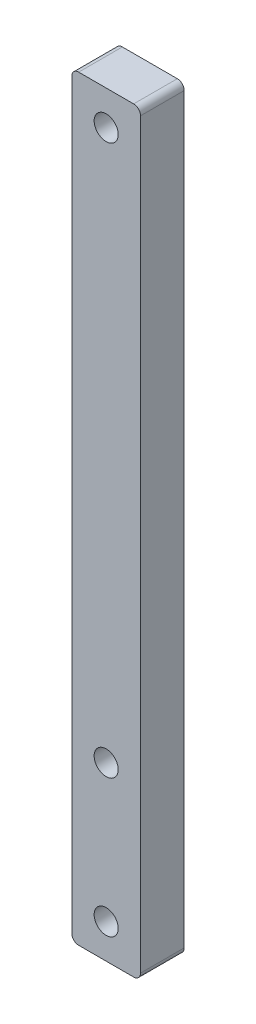
SolidWorks part; units mm, degrees
material "Acrylic (Medium-high impact)"
ref_plane "Front Plane" through (0, 0, 0) normal (0, 0, 1) x (1, 0, 0)
ref_plane "Top Plane" through (0, 0, 0) normal (0, 1, 0) x (1, 0, 0)
ref_plane "Right Plane" through (0, 0, 0) normal (1, 0, 0) x (0, 0, -1)
sketch "Sketch1" plane through (0, 0, 0) normal (0, 0, 1) x (1, 0, 0)
  line L0 (0, 1) -> (0, 109)
  line L1 (10, 1) -> (10, 109)
  line L2 (1, 110) -> (9, 110)
  line L3 (1, 0) -> (9, 0)
  circle A0 centre (5, 105) radius 1.75
  circle A1 centre (5, 5) radius 1.75
  arc A2 (1, 0) -> (0, 1) centre (1, 1) cw
  arc A3 (10, 1) -> (9, 0) centre (9, 1) cw
  arc A4 (0, 109) -> (1, 110) centre (1, 109) cw
  arc A5 (9, 110) -> (10, 109) centre (9, 109) cw
  point P11 (0, 0)
  point P14 (10, 0)
  point P17 (0, 110)
  point P20 (10, 110)
  dimension "D4" = 3.5
  dimension "D7" = 3.5
  dimension "D8" = 5
  dimension "D10" = 1
  dimension "D11" = 1
  dimension "D12" = 1
  dimension "D13" = 1
  dimension "D1" = 110
  dimension "D2" = 110
  dimension "D3" = 10
  dimension "D5" = 5
  dimension "D6" = 5
  dimension "D9" = 5
extrude "Boss-Extrude1" add sketch "Sketch1" along normal blind 6.35
sketch "Sketch2" plane through (0, 0, 6.35) normal (0, 0, 1) x (1, 0, 0)
  line L0 (10, 1) -> (10, 109) construction
  circle A0 centre (5, 25) radius 1.75
  circle A1 centre (5, 5) radius 1.75 construction
  dimension "D1" = 20
  dimension "D2" = 3.5
  dimension "D3" = 5
extrude "Cut-Extrude1" cut sketch "Sketch2" against normal blind 10
